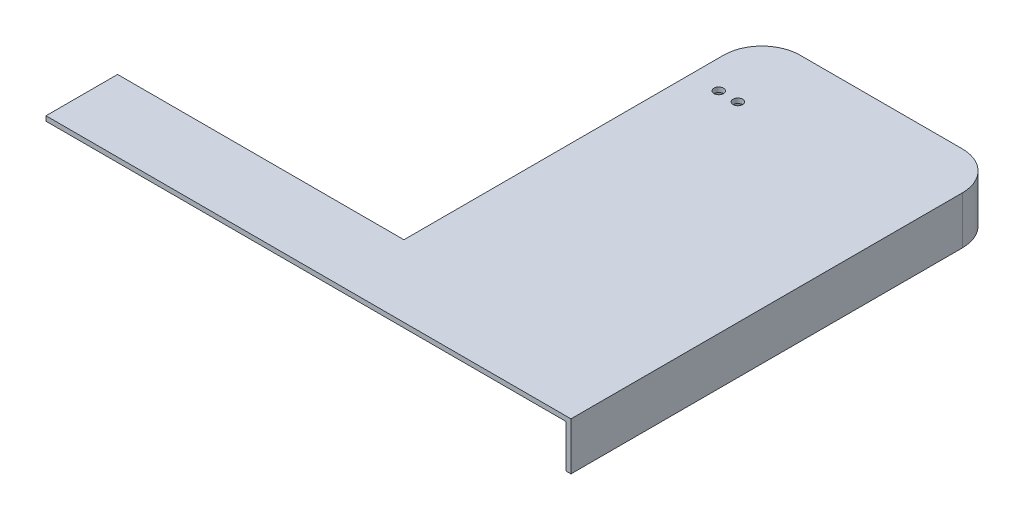
SolidWorks part; units mm, degrees
material "ABS"
ref_plane "Front Plane" through (0, 0, 0) normal (0, 0, 1) x (1, 0, 0)
ref_plane "Top Plane" through (0, 0, 0) normal (0, 1, 0) x (1, 0, 0)
ref_plane "Right Plane" through (0, 0, 0) normal (1, 0, 0) x (0, 0, -1)
sketch "Sketch1" plane through (0, 0, 0) normal (0, 1, 0) x (1, 0, 0)
  line L1 (-279.4, -203.2) -> (279.4, -203.2)
  line L2 (-279.4, -203.2) -> (-279.4, 203.2)
  line L3 (-279.4, 203.2) -> (279.4, 203.2)
  line L4 (279.4, -203.2) -> (279.4, 203.2)
  line L5 (-279.4, -203.2) -> (279.4, 203.2) construction
  line L6 (-279.4, 203.2) -> (279.4, -203.2) construction
  line L7 (-152.4, 203.2) -> (152.4, 203.2)
  line L8 (-152.4, 203.2) -> (-152.4, 12.7)
  line L9 (-152.4, 12.7) -> (152.4, 12.7)
  line L10 (152.4, 203.2) -> (152.4, 12.7)
  point P0 (0, 0)
  dimension "D1" = 558.8
  dimension "D2" = 406.4
  dimension "D3" = 127
  dimension "D4" = 127
  dimension "D5" = 190.5
extrude "Boss-Extrude1" add sketch "Sketch1" along normal blind 25.4 contours L3 L10 L9 L8 L2 L1 L4
fillet "Fillet1" radius 20.32 4 edges at (279.4, 12.7, -203.2) (152.4, 12.7, -203.2) (-279.4, 12.7, -203.2) (-152.4, 12.7, -203.2)
shell "Shell1" thickness 2.54
sketch "Sketch2" plane through (0, 25.4, 0) normal (0, 1, 0) x (1, 0, 0)
  line L0 (-317.2722, 165.1) -> (360.7838, 165.1) construction
  line L1 (-279.4, -203.2) -> (279.4, -203.2) construction
  line L2 (152.4, 182.88) -> (152.4, 12.7) construction
  line L3 (-152.4, 182.88) -> (-152.4, 12.7) construction
  circle A0 centre (-177.72, 165.1) radius 2.54
  circle A1 centre (-167.56, 165.1) radius 2.54
  circle A2 centre (167.56, 165.1) radius 2.54
  circle A3 centre (177.72, 165.1) radius 2.54
  point P12 (157.4, 165.1)
  point P13 (-157.4, 165.1)
  dimension "D2" = 10.16
  dimension "D8" = 5.08
  dimension "D1" = 368.3
  dimension "D3" = 10.16
  dimension "D4" = 10.16
  dimension "D5" = 10.16
  dimension "D6" = 5
  dimension "D7" = 5
extrude "Cut-Extrude1" cut sketch "Sketch2" against normal through all
sketch "Sketch3" plane through (0, 25.4, 0) normal (0, 1, 0) x (1, 0, 0)
  line L0 (279.4, -203.2) -> (279.4, 182.88) construction
  line L1 (279.4, 203.2) -> (0, 203.2)
  line L2 (279.4, 203.2) -> (279.4, -25.4)
  line L3 (279.4, -25.4) -> (0, -25.4)
  line L4 (0, 203.2) -> (0, -25.4)
  line L5 (172.72, 203.2) -> (259.08, 203.2) construction
  line L6 (0, 203.2) -> (-296.6335, 203.2)
  line L8 (-296.6335, 203.2) -> (-305.6265, -253.0885)
  line L9 (-305.6265, -253.0885) -> (279.4, -253.0885)
  line L10 (279.4, -253.0885) -> (279.4, -25.4)
  dimension "D1" = 279.4
  dimension "D2" = 228.6
extrude "Cut-Extrude2" cut sketch "Sketch3" against normal through all
